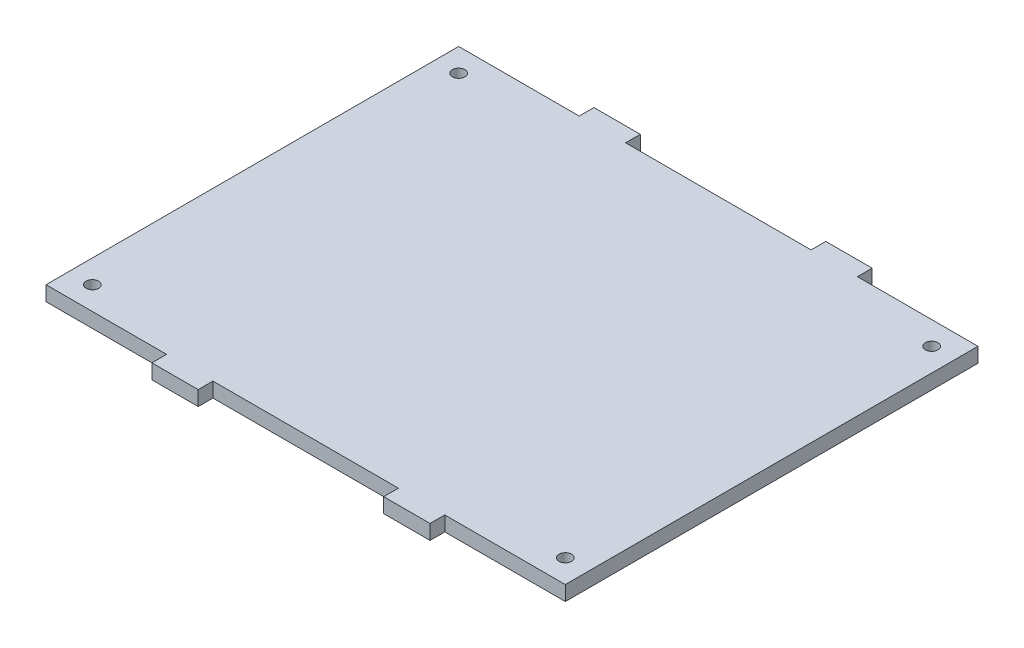
SolidWorks part; units mm, degrees
ref_plane "Front Plane" through (0, 0, 0) normal (0, 0, 1) x (1, 0, 0)
ref_plane "Top Plane" through (0, 0, 0) normal (0, 1, 0) x (1, 0, 0)
ref_plane "Right Plane" through (0, 0, 0) normal (1, 0, 0) x (0, 0, -1)
sketch "Sketch1" plane through (0, 0, 0) normal (0, 1, 0) x (1, 0, 0)
  line L1 (-56, -47.675) -> (56, -47.675)
  line L2 (-56, -47.675) -> (-56, 47.675)
  line L3 (-56, 47.675) -> (56, 47.675)
  line L4 (56, -47.675) -> (56, 47.675)
  line L5 (-56, -47.675) -> (56, 47.675) construction
  line L6 (-56, 47.675) -> (56, -47.675) construction
  point P0 (0, 0)
  dimension "D1" = 112
  dimension "D2" = 95.35
extrude "Boss-Extrude1" add sketch "Sketch1" along normal blind 3.175
sketch "Sketch2" plane through (0, 3.175, 0) normal (0, 1, 0) x (1, 0, 0)
  line L0 (56, 47.675) -> (-56, 47.675) construction
  line L1 (-20, 47.675) -> (20, 47.675)
  line L2 (-20, 47.675) -> (-20, 44.5)
  line L3 (-20, 44.5) -> (20, 44.5)
  line L4 (20, 47.675) -> (20, 44.5)
  line L6 (56, -47.675) -> (56, 47.675) construction
  line L7 (30, 47.675) -> (56, 47.675)
  line L8 (30, 47.675) -> (30, 44.5)
  line L9 (30, 44.5) -> (56, 44.5)
  line L10 (56, 47.675) -> (56, 44.5)
  line L11 (-56, -47.675) -> (56, -47.675) construction
  line L12 (-56, 47.675) -> (-30, 47.675)
  line L13 (-56, 47.675) -> (-56, 44.5)
  line L14 (-56, 44.5) -> (-30, 44.5)
  line L15 (-30, 47.675) -> (-30, 44.5)
  line L16 (-20, -47.675) -> (20, -47.675)
  line L17 (-20, -47.675) -> (-20, -44.5)
  line L18 (-20, -44.5) -> (20, -44.5)
  line L19 (20, -47.675) -> (20, -44.5)
  line L21 (-30, -44.5) -> (-56, -44.5)
  line L22 (-30, -44.5) -> (-30, -47.675)
  line L23 (-30, -47.675) -> (-56, -47.675)
  line L24 (-56, -44.5) -> (-56, -47.675)
  line L25 (30, -44.5) -> (56, -44.5)
  line L26 (30, -44.5) -> (30, -47.675)
  line L27 (30, -47.675) -> (56, -47.675)
  line L28 (56, -44.5) -> (56, -47.675)
  dimension "D1" = 40
  dimension "D2" = 3.175
  dimension "D3" = 20
  dimension "D4" = 10
  dimension "D5" = 10
  dimension "D6" = 40
  dimension "D7" = 20
  dimension "D8" = 3.175
extrude "Cut-Extrude1" cut sketch "Sketch2" against normal through all
sketch "Sketch3" plane through (0, 3.175, 0) normal (0, 1, 0) x (1, 0, 0)
  circle A0 centre (-51, 39.5) radius 1.35
  circle A1 centre (51, 39.5) radius 1.35
  circle A2 centre (-51, -39.5) radius 1.35
  circle A3 centre (51, -39.5) radius 1.35
  dimension "D1" = 102
  dimension "D3" = 79
  dimension "D2" = 51
  dimension "D5" = 39.5
extrude "Cut-Extrude2" cut sketch "Sketch3" against normal through all
